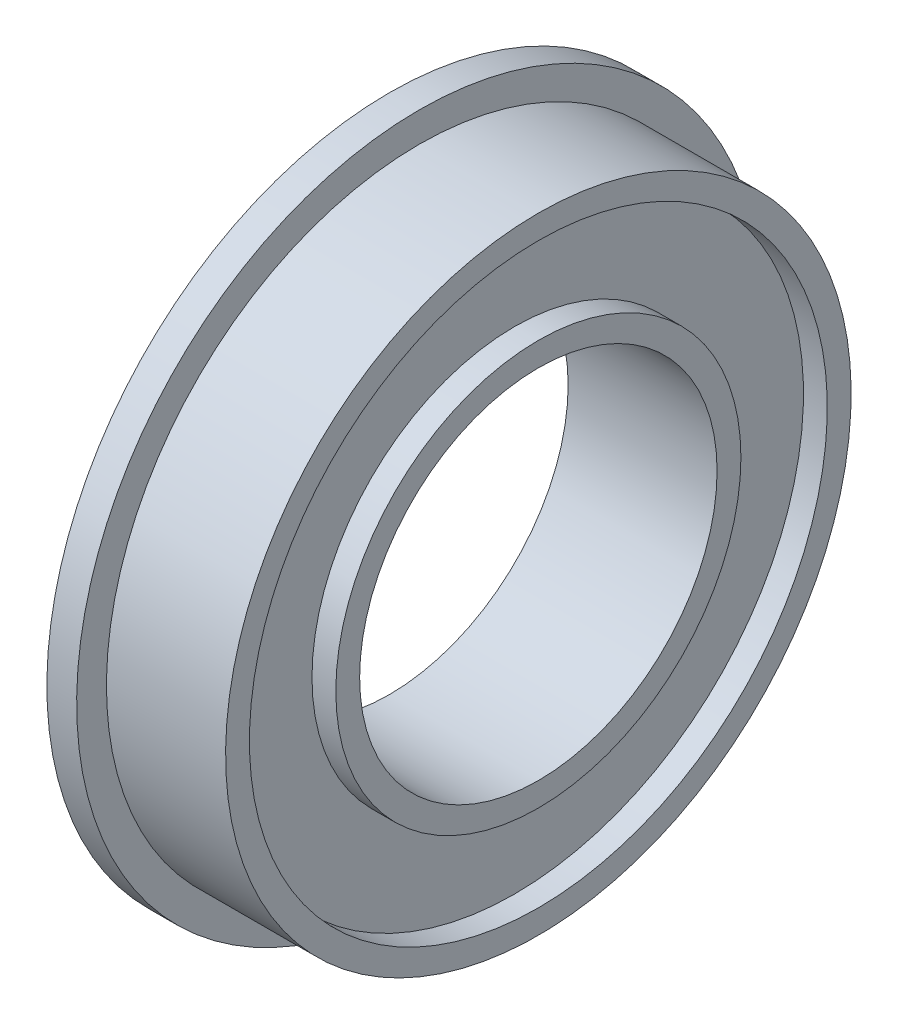
SolidWorks part; units mm, degrees
material "AISI 304"
ref_plane "前视基准面" through (0, 0, 0) normal (0, 0, 1) x (1, 0, 0)
ref_plane "上视基准面" through (0, 0, 0) normal (0, 1, 0) x (1, 0, 0)
ref_plane "右视基准面" through (0, 0, 0) normal (1, 0, 0) x (0, 0, -1)
sketch "草图1" plane through (0, 0, 0) normal (0, 0, 1) x (1, 0, 0)
  line L0 (0, -3.1317) -> (-7.9024, -3.1317) construction
  line L1 (0, 8.3683) -> (1, 8.3683)
  line L2 (1, 8.3683) -> (1, 7.3683)
  line L3 (1, 7.3683) -> (5, 7.3683)
  line L4 (5, 7.3683) -> (5, 6.5683)
  line L5 (5, 6.5683) -> (4.2, 6.5683)
  line L6 (4.2, 6.5683) -> (4.2, 3.6683)
  line L7 (4.2, 3.6683) -> (5, 3.6683)
  line L8 (5, 3.6683) -> (5, 2.8683)
  line L9 (5, 2.8683) -> (0, 2.8683)
  line L10 (0, 2.8683) -> (0, 3.6683)
  line L11 (0, 3.6683) -> (0.8, 3.6683)
  line L12 (0.8, 3.6683) -> (0.8, 6.5683)
  line L13 (0.8, 6.5683) -> (0, 6.5683)
  line L14 (0, 6.5683) -> (0, 8.3683)
  dimension "D1" = 0.8
  dimension "D2" = 11.5
  dimension "D3" = 6
  dimension "D4" = 5
  dimension "D5" = 1
  dimension "D6" = 1
revolve "旋转1" add sketch "草图1" angle 360 about L0
move or copy body "实体-移动/复制1" [suppressed] bodies to move or copy 106
